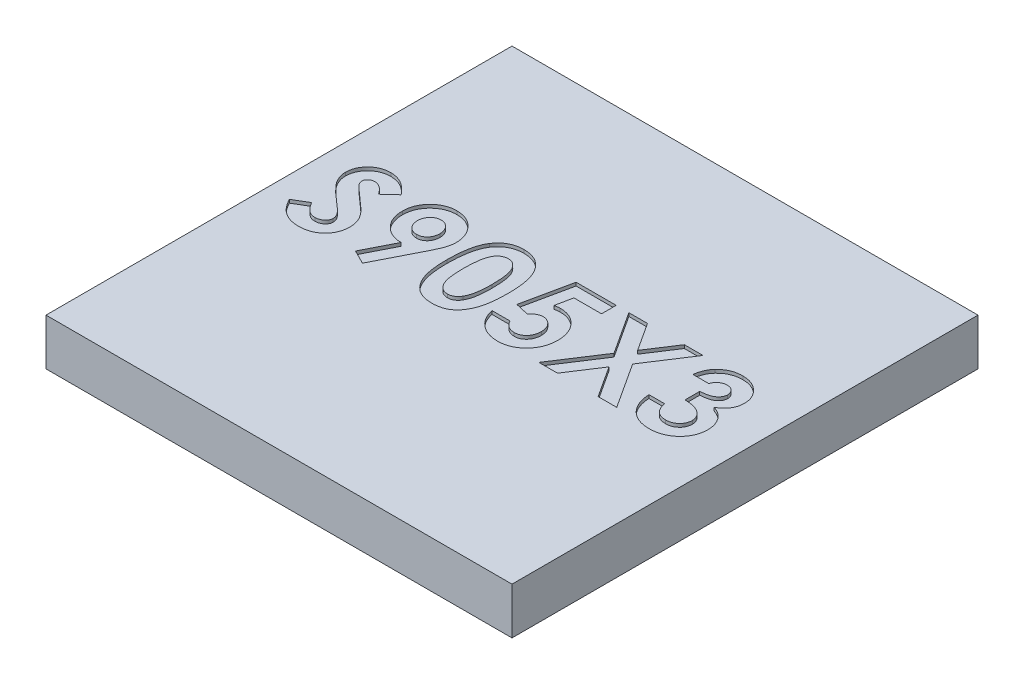
SolidWorks part; units mm, degrees
ref_plane "Front" through (0, 0, 0) normal (0, 0, 1) x (1, 0, 0)
ref_plane "Top" through (0, 0, 0) normal (0, 1, 0) x (1, 0, 0)
ref_plane "Right" through (0, 0, 0) normal (1, 0, 0) x (0, 0, -1)
sketch "Esquisse1" plane through (0, 0, 0) normal (0, 1, 0) x (1, 0, 0)
  line L1 (0, 0) -> (14, 0)
  line L2 (0, 0) -> (0, 14)
  line L3 (0, 14) -> (14, 14)
  line L4 (14, 0) -> (14, 14)
  dimension "D1" = 14
  dimension "D2" = 14
extrude "Boss.-Extru.1" add sketch "Esquisse1" along normal blind 1.4
sketch "Esquisse2" plane through (0, 1.4, 0) normal (0, 1, 0) x (1, 0, 0)
  text T0 "<b>S905X3</b>" font "Century Gothic" height in points 10
extrude "Enlèv. mat.-Extru.1" cut sketch "Esquisse2" against normal blind 0.1
